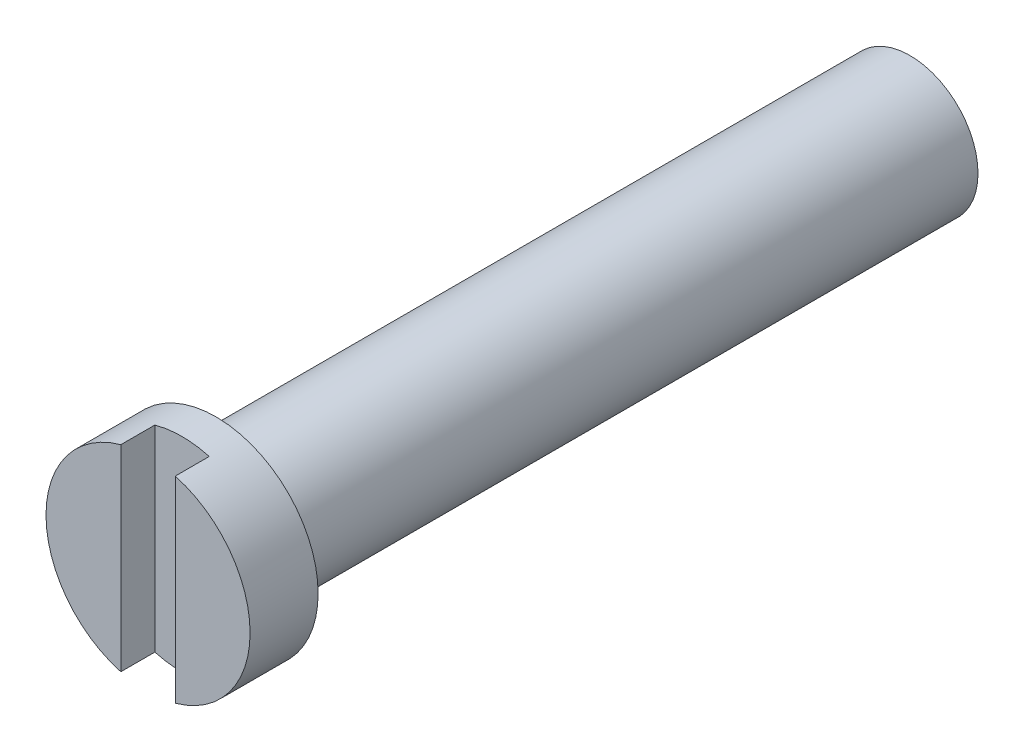
SolidWorks part; units mm, degrees
ref_plane "Front Plane" through (0, 0, 0) normal (0, 0, 1) x (1, 0, 0)
ref_plane "Top Plane" through (0, 0, 0) normal (0, 1, 0) x (1, 0, 0)
ref_plane "Right Plane" through (0, 0, 0) normal (1, 0, 0) x (0, 0, -1)
sketch "Sketch2" plane through (0, 0, 0) normal (0, 0, 1) x (1, 0, 0)
  circle A0 centre (0, 0) radius 1
  dimension "D1" = 2
extrude "Boss-Extrude1" add sketch "Sketch2" along normal blind 10.2
sketch "Sketch3" plane through (0, 0, 10.2) normal (0, 0, 1) x (1, 0, 0)
  circle A0 centre (0, 0) radius 1.5
  dimension "D1" = 3
extrude "Boss-Extrude2" add sketch "Sketch3" along normal blind 1
sketch "Sketch4" plane through (0, 0, 11.2) normal (0, 0, 1) x (1, 0, 0)
  line L0 (0, -1.5) -> (0, 1.5) construction
  line L1 (0.4, 1.4457) -> (0.4, -1.4457)
  line L2 (-0.4, 1.4457) -> (-0.4, -1.4457)
  circle A0 centre (0, 0) radius 1.5 construction
  arc A1 (-0.4, -1.4457) -> (0.4, -1.4457) centre (0, 0) ccw
  arc A2 (0.4, 1.4457) -> (-0.4, 1.4457) centre (0, 0) ccw
  dimension "D1" = 0.4
extrude "Cut-Extrude1" cut sketch "Sketch4" against normal blind 0.5
